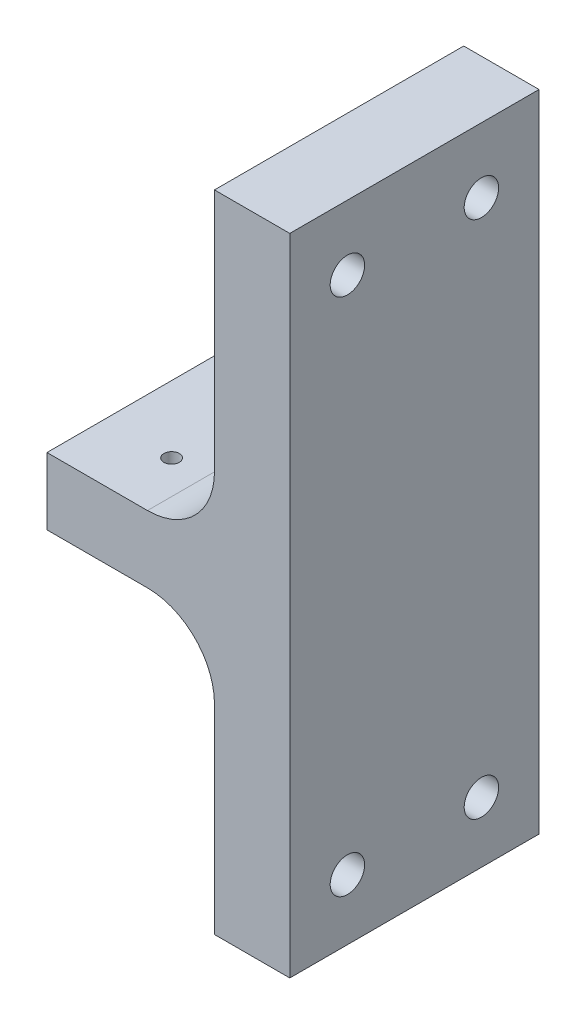
SolidWorks part; units mm, degrees
ref_plane "Front Plane" through (0, 0, 0) normal (0, 0, 1) x (1, 0, 0)
ref_plane "Top Plane" through (0, 0, 0) normal (0, 1, 0) x (1, 0, 0)
ref_plane "Right Plane" through (0, 0, 0) normal (1, 0, 0) x (0, 0, -1)
sketch "Sketch1" plane through (0, 0, 0) normal (0, 1, 0) x (1, 0, 0)
  line L0 (0, 12.7) -> (0, -12.7) construction
  line L1 (-12.7, -23.622) -> (12.7, -23.622)
  line L2 (-12.7, -23.622) -> (-12.7, 23.622)
  line L3 (-12.7, 23.622) -> (12.7, 23.622)
  line L5 (-12.7, -23.622) -> (12.7, 23.622) construction
  line L6 (-12.7, 23.622) -> (12.7, -23.622) construction
  line L8 (12.7, 23.622) -> (19.05, 23.622)
  line L10 (12.7, -23.622) -> (19.05, -23.622)
  line L11 (19.05, 23.622) -> (19.05, -23.622)
  circle A0 centre (0, 12.7) radius 1.4605
  circle A1 centre (0, -12.7) radius 1.4605
  point P0 (0, 0)
  dimension "D4" = 2.921
  dimension "D1" = 47.244
  dimension "D2" = 25.4
  dimension "D3" = 25.4
  dimension "D5" = 6.35
extrude "Boss-Extrude1" add sketch "Sketch1" along normal blind 12.7
sketch "Sketch2" plane through (19.05, 0, 0) normal (1, 0, 0) x (0, 0, -1)
  line L0 (23.622, 12.7) -> (23.622, 0) construction
  line L2 (-23.622, 0) -> (-23.622, -50.546)
  line L3 (-23.622, -50.546) -> (23.622, -50.546)
  line L4 (23.622, 71.6788) -> (23.622, -50.546)
  line L7 (-23.622, 0) -> (-23.622, 71.6788)
  line L8 (-23.622, 71.6788) -> (23.622, 71.6788)
  point P5 (23.622, 51.7491)
  point P6 (-23.622, 0)
  point P9 (0, 0)
  point P11 (-23.622, 0)
  point P12 (23.622, 2.2054)
  dimension "D1" = 50.546
  dimension "D2" = 71.6788
extrude "Boss-Extrude2" add sketch "Sketch2" along normal blind 14.2748
fillet "Fillet1" radius 12.7 2 edges at (19.05, 12.7, 0) (19.05, 0, 0)
sketch "Sketch3" plane through (33.3248, 0, 0) normal (1, 0, 0) x (0, 0, -1)
  line L0 (-12.7, 59.3852) -> (12.7, 59.3852) construction
  line L2 (12.7, 39.0398) -> (-12.7, 39.0398) construction
  line L3 (12.7, 39.0398) -> (12.7, -39.0398) construction
  line L4 (12.7, -39.0398) -> (-12.7, -39.0398) construction
  line L5 (-12.7, 39.0398) -> (-12.7, -39.0398) construction
  line L6 (12.7, 39.0398) -> (-12.7, -39.0398) construction
  line L7 (12.7, -39.0398) -> (-12.7, 39.0398) construction
  line L8 (-12.7, 39.0398) -> (12.7, 39.0398) construction
  line L9 (-12.7, 39.0398) -> (-12.7, 59.3852) construction
  line L11 (12.7, 39.0398) -> (12.7, 59.3852) construction
  circle A3 centre (-12.7, -39.0398) radius 3.2639
  circle A5 centre (12.7, -39.0398) radius 3.2639
  circle A10 centre (-12.7, 59.3852) radius 3.2639
  circle A11 centre (12.7, 59.3852) radius 3.2639
  point P0 (0, 0)
  point P2 (12.7, -39.0398)
  point P5 (-12.7, -39.0398)
  dimension "D3" = 6.5278
  dimension "D1" = 25.4
  dimension "D2" = 39.0398
  dimension "D4" = 20.3454
extrude "Cut-Extrude1" cut sketch "Sketch3" against normal through all
